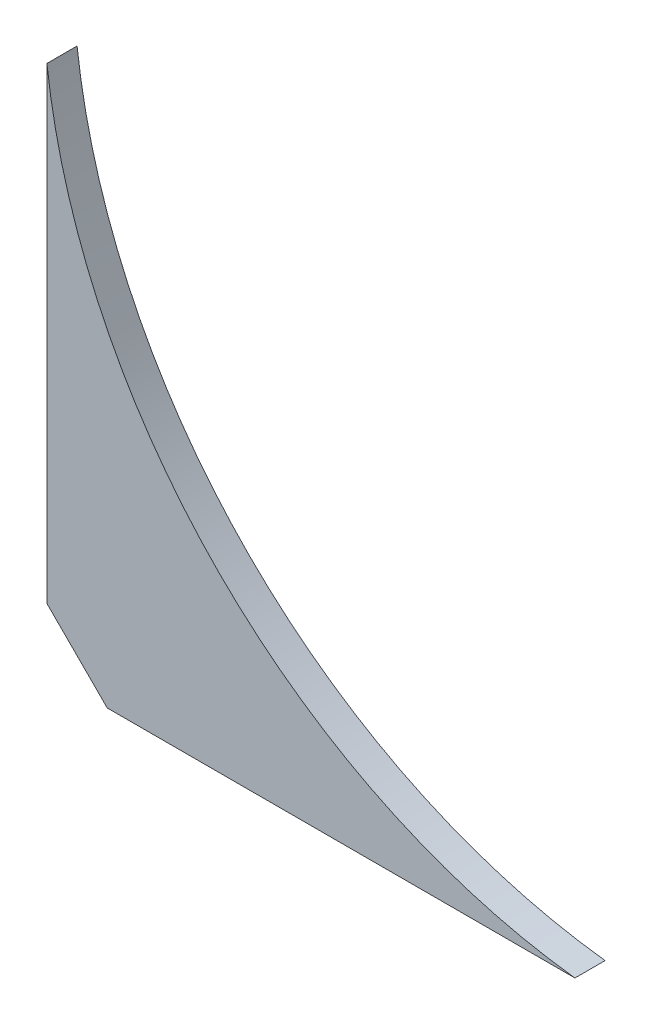
SolidWorks part; units mm, degrees
material "Plain Carbon Steel"
ref_plane "Front Plane" through (0, 0, 0) normal (0, 0, 1) x (1, 0, 0)
ref_plane "Top Plane" through (0, 0, 0) normal (0, 1, 0) x (1, 0, 0)
ref_plane "Right Plane" through (0, 0, 0) normal (1, 0, 0) x (0, 0, -1)
sketch "Sketch1" plane through (0, 0, 0) normal (0, 0, 1) x (1, 0, 0)
  line L0 (-50.1632, 132.915) -> (-50.1632, -22.085)
  line L1 (-30.1632, -42.085) -> (124.8368, -42.085)
  line L2 (-50.1632, -22.085) -> (-30.1632, -42.085)
  arc A0 (-50.1632, 132.915) -> (124.8368, -42.085) centre (148.4392, 156.5175) ccw
  point P1 (-50.1632, -42.085)
  dimension "D1" = 200
  dimension "D2" = 175
  dimension "D3" = 175
extrude "Boss-Extrude1" add sketch "Sketch1" along normal mid plane 10
